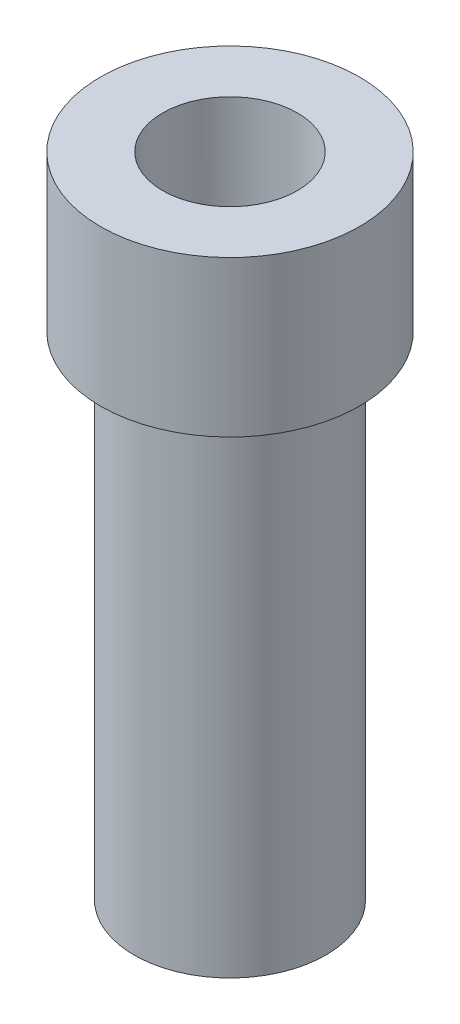
SolidWorks part; units mm, degrees
ref_plane "Front Plane" through (0, 0, 0) normal (0, 0, 1) x (1, 0, 0)
ref_plane "Top Plane" through (0, 0, 0) normal (0, 1, 0) x (1, 0, 0)
ref_plane "Right Plane" through (0, 0, 0) normal (1, 0, 0) x (0, 0, -1)
sketch "Sketch1" plane through (0, 0, 0) normal (0, 1, 0) x (1, 0, 0)
  circle A0 centre (0, 0) radius 6.5
  circle A1 centre (0, 0) radius 9.25
  dimension "D1" = 13
  dimension "D2" = 18.5
extrude "Boss-Extrude1" add sketch "Sketch1" along normal blind 62.5
sketch "Sketch3" plane through (0, 62.5, 0) normal (0, 1, 0) x (1, 0, 0)
  circle A0 centre (0, 0) radius 12.5
  circle A1 centre (0, 0) radius 6.5
  dimension "D1" = 25
extrude "Boss-Extrude2" add sketch "Sketch3" against normal blind 15
sketch "Sketch4" plane through (0, 0, 0) normal (0, -1, 0) x (1, 0, 0)
  circle A0 centre (0, 0) radius 9.25 construction
  circle A1 centre (0, 0) radius 6.5 construction
  circle A2 centre (0, 0) radius 9.25
  circle A3 centre (0, 0) radius 6.5
extrude "Boss-Extrude3" add sketch "Sketch4" along normal blind 2.51
sketch "Sketch5" plane through (0, 47.5, 0) normal (0, -1, 0) x (1, 0, 0)
  circle A0 centre (0, 0) radius 12.5 construction
  circle A1 centre (0, 0) radius 9.25 construction
  circle A2 centre (0, 0) radius 12.5
  circle A3 centre (0, 0) radius 9.25
extrude "Boss-Extrude4" add sketch "Sketch5" along normal blind 2.51
sketch "Sketch6" plane through (0, 62.5, 0) normal (0, 1, 0) x (1, 0, 0)
  circle A0 centre (0, 0) radius 12.5 construction
  circle A1 centre (0, 0) radius 6.5 construction
  circle A2 centre (0, 0) radius 12.5
  circle A3 centre (0, 0) radius 6.5
extrude "Cut-Extrude1" cut sketch "Sketch6" against normal blind 2.51
